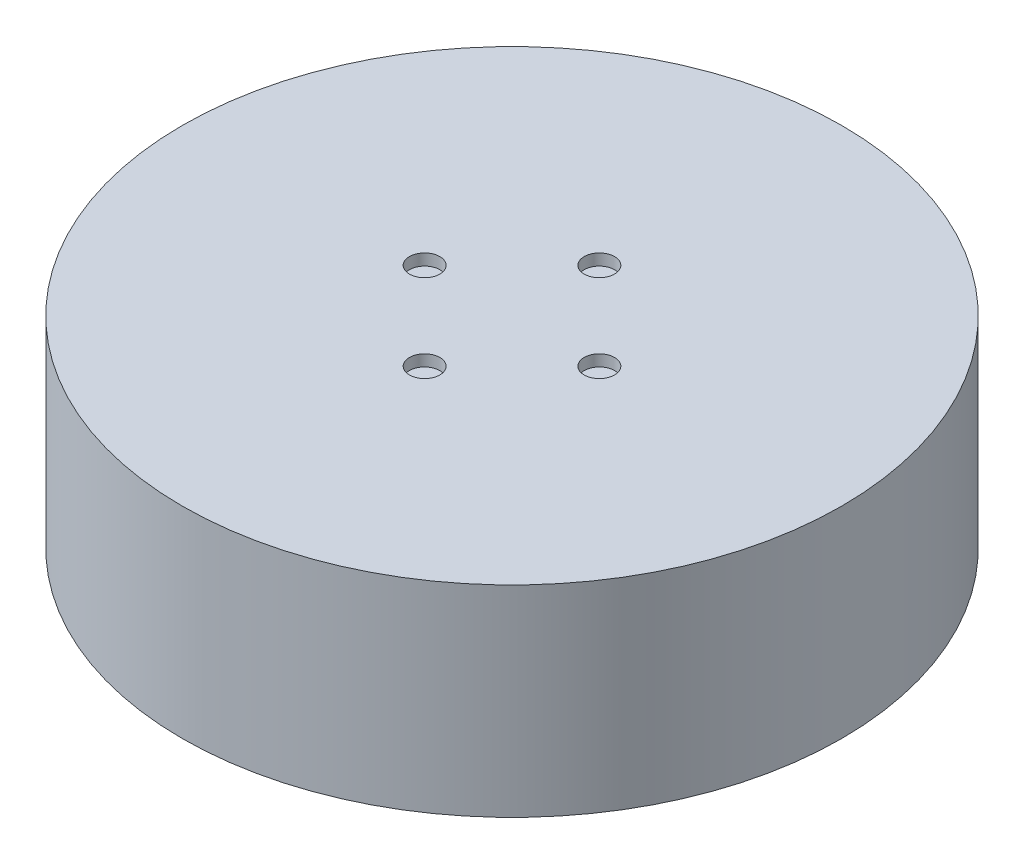
SolidWorks part; units mm, degrees
ref_plane "Front Plane" through (0, 0, 0) normal (0, 0, 1) x (1, 0, 0)
ref_plane "Top Plane" through (0, 0, 0) normal (0, 1, 0) x (1, 0, 0)
ref_plane "Right Plane" through (0, 0, 0) normal (1, 0, 0) x (0, 0, -1)
sketch "Sketch1" plane through (0, 0, 0) normal (0, 1, 0) x (1, 0, 0)
  circle A0 centre (0, 0) radius 43.4
  dimension "D1" = 86.8
extrude "Boss-Extrude1" add sketch "Sketch1" along normal blind 26.5
sketch "Sketch2" plane through (0, 0, 0) normal (0, -1, 0) x (1, 0, 0)
  circle A0 centre (0, 0) radius 16 construction
  circle A1 centre (0, 16) radius 2
  circle A2 centre (16, 0) radius 2
  circle A3 centre (0, -16) radius 2
  circle A4 centre (-16, 0) radius 2
  point P14 (0, 0)
  dimension "D1" = 32
  dimension "D2" = 4
  dimension "D3" = 4
extrude "Cut-Extrude1" cut sketch "Sketch2" against normal blind 1.5
sketch "Sketch3" plane through (0, 0, 0) normal (0, -1, 0) x (1, 0, 0)
  line L0 (0, 0) -> (0, 16) construction
  line L1 (0, 16) -> (16, 0) construction
  line L2 (16, 0) -> (0, 0) construction
  line L3 (0, 0) -> (21.2132, 21.2132) construction
  line L4 (17.6777, 24.7487) -> (24.7487, 17.6777) construction
  line L5 (20.5061, 27.5772) -> (27.5772, 20.5061) construction
  line L6 (14.8492, 21.9203) -> (21.9203, 14.8492) construction
  line L7 (19.799, 26.8701) -> (26.8701, 19.799)
  line L8 (15.5563, 22.6274) -> (22.6274, 15.5563)
  arc A0 (20.5061, 27.5772) -> (14.8492, 21.9203) centre (17.6777, 24.7487) ccw construction
  arc A1 (21.9203, 14.8492) -> (27.5772, 20.5061) centre (24.7487, 17.6777) ccw construction
  arc A2 (22.6274, 15.5563) -> (26.8701, 19.799) centre (24.7487, 17.6777) ccw
  arc A3 (19.799, 26.8701) -> (15.5563, 22.6274) centre (17.6777, 24.7487) ccw
  point P9 (21.2132, 21.2132)
  dimension "D3" = 4
  dimension "D1" = 30
  dimension "D2" = 10
  dimension "D4" = 1
extrude "Boss-Extrude2" add sketch "Sketch3" along normal blind 6
sketch "Sketch4" plane through (0, 26.5, 0) normal (0, 1, 0) x (1, 0, 0)
  circle A0 centre (0, 0) radius 11.5 construction
  circle A1 centre (0, 11.5) radius 2
  circle A2 centre (11.5, 0) radius 2
  circle A3 centre (0, -11.5) radius 2
  circle A4 centre (-11.5, 0) radius 2
  point P14 (0, 0)
  dimension "D2" = 4
  dimension "D3" = 4
  dimension "D1" = 23
extrude "Cut-Extrude2" cut sketch "Sketch4" against normal blind 1.5
equation "\"Np\"= 45"
equation "\"module\"= 0.7"
equation "\"pressure angle\"= 20.0deg"
equation "\"h_a\"= 0.7"
equation "\"h_b\"= 0.875"
equation "\"clr_tip_root\"= 0.17500000000000004"
equation "\"dp_p\"= 31.499999999999996"
equation "\"db_p\"= 29.600317554756113"
equation "\"fw_p\"= 8.0"
equation "\"alpha_p\"= 0.8539582918412343"
equation "\"beta_p\"= 2.2920834163175314"
equation "\"Nr\"= 108"
equation "\"pressure_angle\"= 20.0deg"
equation "\"h_f\"= 0.875"
equation "\"dp_r\"= 75.6"
equation "\"db_r\"= 71.04076213141467"
equation "\"fw_r\"= 8.0"
equation "\"alpha_r\"= 0.8539582918412449"
equation "\"beta_r\"= 3.374583250349157"
equation "\"bearing_ID\"= 55"
equation "\"bearing_OD\"= 72"
equation "\"bearing_height\"= 9"
equation "\"clearance_planet\"= 1.5"
equation "\"case_dist\"= 6.5"
equation "\"Motor_case_OD_max\"= 111.3"
equation "\"case_mounting_PCD\"= 103.8"
equation "\"bearing mount thickness\"= 8"
equation "\"case_mounting_hole_dia\"= 3"
equation "\"output_mounting_PCD\"= 80"
equation "\"output_mounting_hole_dia\"= 4"
equation "\"clearance_case_mount_holes_shell_thickness\"= 1"
equation "\"motor_case_OD_base\"= 101.8"
equation "\"sec_carrier_thickness\"= 5"
equation "\"sun_coupler_hub_thickness\"= 4"
equation "\"clearance_sun_coupler_sec_carrier\"= 1.5"
equation "\"clearance_motor_and_case\"= 5"
equation "\"motor_OD\"= 86.8"
equation "\"Motor_case_thickness\"= 2.5"
equation "\"Motor_case_ID\"= 96.8"
equation "\"case_mounting_hole_shift\"= 1.0"
equation "\"output_mounting_nut_wrench_size\"= 7"
equation "\"output_mounting_nut_thickness\"= 3.2"
equation "\"case_mounting_hole_allen_socket_dia\"= 5.5"
equation "\"output_mounting_nut_depth\"= 3"
equation "\"case_mounting_bolt_depth\"= 4.5"
equation "\"Ns\"= 18"
equation "\"ring_radial_thickness\"= 5.0"
equation "\"ring_OD\"= 85.6"
equation "\"ring_to_chamfer_clearance\"= 2"
equation "\"Motor_case_OD_base_to_chamfer\"= 5"
equation "\"pattern_offset_from_motor_case_OD_base\"= 3"
equation "\"pattern_bulge_dia\"= 3"
equation "\"pattern_num_bulge\"= 18"
equation "\"pattern_depth\"= 2"
equation "\"motor_height\"= 26.5"
equation "\"case_mounting_wrench_size\"= 5.5"
equation "\"case_mounting_nut_clearance\"= 2"
equation "\"base_plate_thickness\"= 4"
equation "\"case_mounting_nut_thickness\"= 2.4"
equation "\"case_mounting_surface_height\"= 4"
equation "\"motor_mount_hole_PCD\"= 32"
equation "\"motor_mount_hole_dia\"= 4"
equation "\"motor_mount_hole_num\"= 4"
equation "\"central_hole_offset_from_motor_mount_PCD\"= 5"
equation "\"wire_slot_dist_from_center\"= 30"
equation "\"wire_slot_length\"= 10"
equation "\"wire_slot_radius\"= 4"
equation "\"driver_upper_holes_dist_from_center\"= 23"
equation "\"driver_lower_holes_dist_from_center\"= 15"
equation "\"driver_side_holes_dist_from_center\"= 20"
equation "\"driver_mount_holes_dia\"= 2.5"
equation "\"driver_mount_inserts_OD\"= 3.5"
equation "\"driver_mount_thickness\"= 1.5"
equation "\"driver_mount_height\"= 4"
equation "\"air_flow_hole_offset\"= 3"
equation "\"num_planet\"= 3"
equation "\"planet_pin_bolt_dia\"= 5"
equation "\"planet_pin_socket_head_dia\"= 8.5"
equation "\"carrier_PCD\"= 44.099999999999994"
equation "\"planet_shaft_dia\"= 8"
equation "\"planet_shaft_step_offset\"= 1"
equation "\"carrier_trapezoidal_support_sun_offset\"= 5"
equation "\"carrier_trapezoidal_support_hole_PCD_offset_bearing_ID\"= 4"
equation "\"carrier_trapezoidal_support_hole_dia\"= 3"
equation "\"carrier_trapezoidal_support_hole_socket_head_dia\"= 5.5"
equation "\"carrier_bearing_step_width\"= 1.5"
equation "\"standard_clearance_1_5mm\"= 1.5"
equation "\"standard_fillet_1_5mm\"= 1.5"
equation "\"sun_shaft_bearing_OD\"= 16"
equation "\"sun_shaft_bearing_width\"= 5"
equation "\"standard_bearing_insertion_chamfer\"= 0.5"
equation "\"carrier_trapezoidal_support_hole_wrench_size\"= 5.5"
equation "\"planet_pin_bolt_wrench_size\"= 8"
equation "\"planet_bearing_OD\"= 12"
equation "\"planet_bearing_width\"= 3.5"
equation "\"planet_bore\"= 10"
equation "\"D1@Boss-Extrude1\"=\"motor_height\""
equation "\"D1@Sketch1\"=\"motor_OD\""
equation "\"D1@Sketch2\"=\"motor_mount_hole_PCD\""
equation "\"D2@Sketch2\"=\"motor_mount_hole_dia\""
equation "\"D3@Sketch2\"=\"motor_mount_hole_num\""
equation "\"D1@Cut-Extrude1\"=\"standard_clearance_1_5mm\""
equation "\"D1@Sketch3\"=\"wire_slot_dist_from_center\""
equation "\"D2@Sketch3\"=\"wire_slot_length\""
equation "\"D3@Sketch3\"=\"wire_slot_radius\""
equation "\"D1@Boss-Extrude2\"=\"standard_clearance_1_5mm\"*4"
equation "\"motor_output_hole_PCD\"= 23"
equation "\"motor_output_hole_dia\"= 4"
equation "\"motor_output_hole_num\"= 4"
equation "\"D1@Sketch4\"=\"motor_output_hole_PCD\""
equation "\"D2@Sketch4\"=\"motor_output_hole_dia\""
equation "\"D3@Sketch4\"=\"motor_output_hole_num\""
equation "\"D1@Cut-Extrude2\"=\"standard_clearance_1_5mm\""
